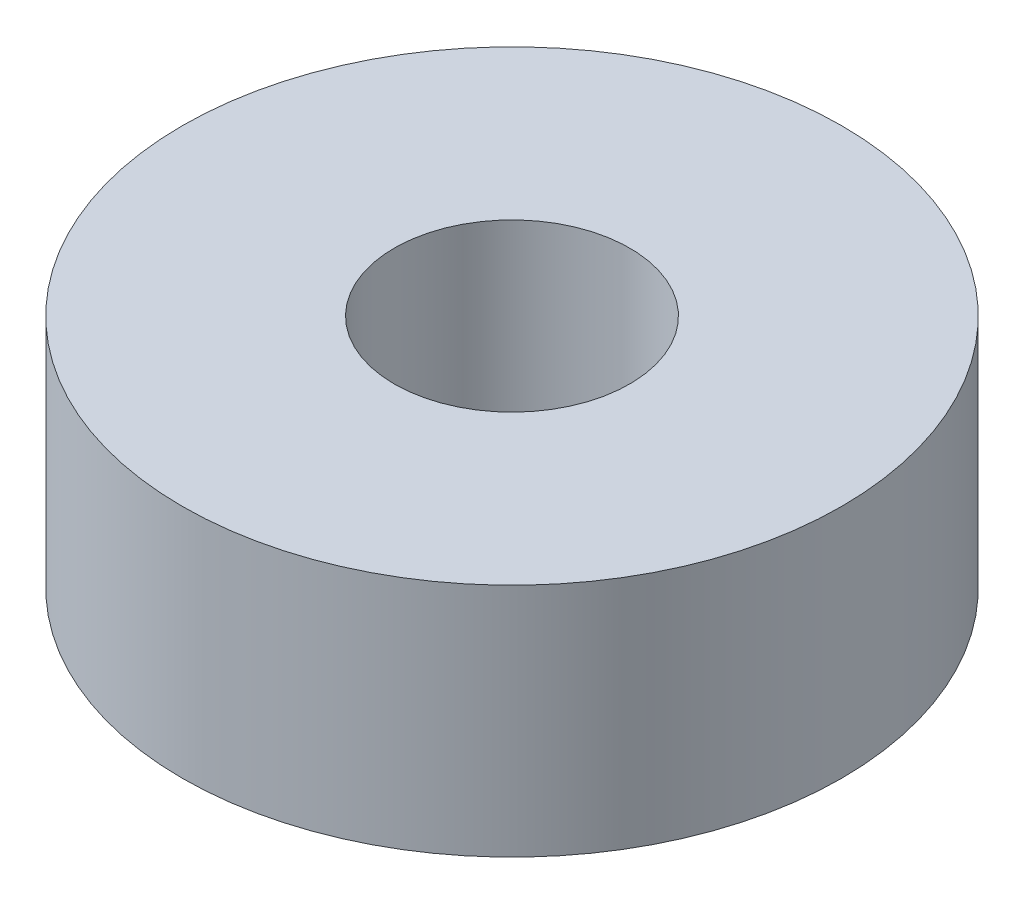
SolidWorks part; units mm, degrees
ref_plane "Front Plane" through (0, 0, 0) normal (0, 0, 1) x (1, 0, 0)
ref_plane "Top Plane" through (0, 0, 0) normal (0, 1, 0) x (1, 0, 0)
ref_plane "Right Plane" through (0, 0, 0) normal (1, 0, 0) x (0, 0, -1)
sketch "Sketch1" plane through (0, 0, 0) normal (0, 1, 0) x (1, 0, 0)
  circle A0 centre (0, 0) radius 2.5
  circle A1 centre (0, 0) radius 7
extrude "Boss-Extrude1" add sketch "Sketch1" along normal blind 5
